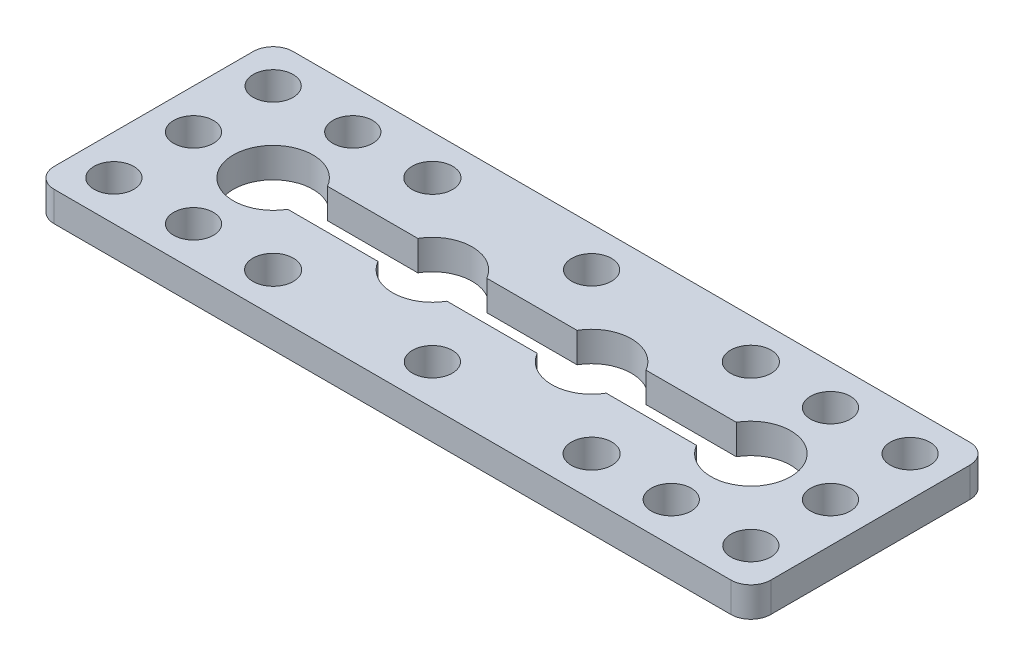
SolidWorks part; units mm, degrees
material "6061 Alloy"
ref_plane "前视基准面" through (0, 0, 0) normal (0, 0, 1) x (1, 0, 0)
ref_plane "上视基准面" through (0, 0, 0) normal (0, 1, 0) x (1, 0, 0)
ref_plane "右视基准面" through (0, 0, 0) normal (1, 0, 0) x (0, 0, -1)
other "Configuration Table"
sketch "Sketch1" plane through (0, 0, 0) normal (0, 1, 0) x (1, 0, 0)
  line L0 (-35.8922, 9.1257) -> (36.1078, 9.1257)
  line L1 (-33.8922, 21.1257) -> (34.1078, 21.1257)
  line L2 (-35.8922, 19.1257) -> (-35.8922, -0.8743)
  line L3 (-33.8922, -2.8743) -> (34.1078, -2.8743)
  line L4 (36.1078, 19.1257) -> (36.1078, -0.8743)
  line L5 (0.1078, 21.1257) -> (0.1078, -2.8743)
  line L9 (-23.8922, 7.1257) -> (24.1078, 7.1257)
  line L12 (-23.8922, 7.1257) -> (-23.8922, 11.1257)
  line L13 (-23.8922, 11.1257) -> (24.1078, 11.1257)
  line L14 (24.1078, 7.1257) -> (24.1078, 11.1257)
  line L15 (-23.8922, 7.1257) -> (24.1078, 11.1257) construction
  line L16 (-23.8922, 11.1257) -> (24.1078, 7.1257) construction
  arc A0 (34.1078, -2.8743) -> (36.1078, -0.8743) centre (34.1078, -0.8743) ccw
  arc A1 (34.1078, 21.1257) -> (36.1078, 19.1257) centre (34.1078, 19.1257) cw
  arc A2 (-35.8922, -0.8743) -> (-33.8922, -2.8743) centre (-33.8922, -0.8743) ccw
  arc A3 (-33.8922, 21.1257) -> (-35.8922, 19.1257) centre (-33.8922, 19.1257) ccw
  circle A4 centre (-31.8922, 17.1257) radius 2
  circle A6 centre (-31.8922, 9.1257) radius 2
  circle A8 centre (-23.8922, 17.1257) radius 2
  circle A9 centre (-15.8922, 17.1257) radius 2.0329
  circle A10 centre (0.1078, 17.1257) radius 2
  circle A11 centre (0.1078, 1.1257) radius 2
  circle A12 centre (-15.8922, 1.1257) radius 2.0329
  circle A13 centre (-23.8922, 1.1257) radius 2
  circle A14 centre (-31.8922, 1.1257) radius 2
  circle A15 centre (24.1078, 17.1257) radius 2
  circle A16 centre (16.1078, 17.1257) radius 2.0329
  circle A17 centre (16.1078, 1.1257) radius 2.0329
  circle A18 centre (24.1078, 1.1257) radius 2
  circle A19 centre (32.1078, 1.1257) radius 2
  circle A20 centre (32.1078, 17.1257) radius 2
  circle A21 centre (32.1078, 9.1257) radius 2
  circle A26 centre (-23.8922, 9.1257) radius 4
  circle A27 centre (-7.8922, 9.1257) radius 4
  circle A28 centre (8.1078, 9.1257) radius 4
  circle A29 centre (24.1078, 9.1257) radius 4
  point P8 (36.1078, 21.1257)
  point P11 (-35.8922, -2.8743)
  point P14 (-35.8922, 21.1257)
  point P51 (0.1078, 9.1257)
  dimension "D3" = 2
  dimension "D4" = 4
  dimension "D6" = 8
  dimension "D8" = 8
  dimension "D9" = 4
  dimension "D10" = 16
  dimension "D1" = 72
  dimension "D2" = 24
  dimension "D5" = 4
  dimension "D7" = 8
extrude "Boss-Extrude2" add sketch "Sketch1" along normal blind 3 contours A27 L9 A26 L0 A6 L2 A2 L3 L5 A11 A13 A12 A14 | A27 L13 L5 A10 L1 A3 L2 L0 A6 A26 A9 A8 A4 | L0 A29 L9 A28 L5 A11 L3 A0 L4 A21 A19 A18 A17 | L13 A29 L0 A21 L4 A1 L1 L5 A10 A28 A16 A15 A20
